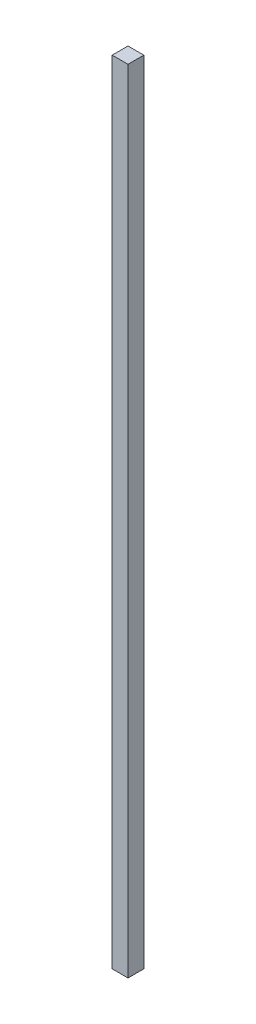
SolidWorks part; units mm, degrees
ref_plane "Front Plane" through (0, 0, 0) normal (0, 0, 1) x (1, 0, 0)
ref_plane "Top Plane" through (0, 0, 0) normal (0, 1, 0) x (1, 0, 0)
ref_plane "Right Plane" through (0, 0, 0) normal (1, 0, 0) x (0, 0, -1)
sketch "Sketch1" plane through (0, 0, 0) normal (0, 1, 0) x (1, 0, 0)
  line L1 (-10, -10) -> (10, -10)
  line L2 (-10, -10) -> (-10, 10)
  line L3 (-10, 10) -> (10, 10)
  line L4 (10, -10) -> (10, 10)
  line L5 (-10, -10) -> (10, 10) construction
  line L6 (-10, 10) -> (10, -10) construction
  point P0 (0, 0)
  dimension "D1" = 20
extrude "Boss-Extrude1" add sketch "Sketch1" along normal blind 1000
